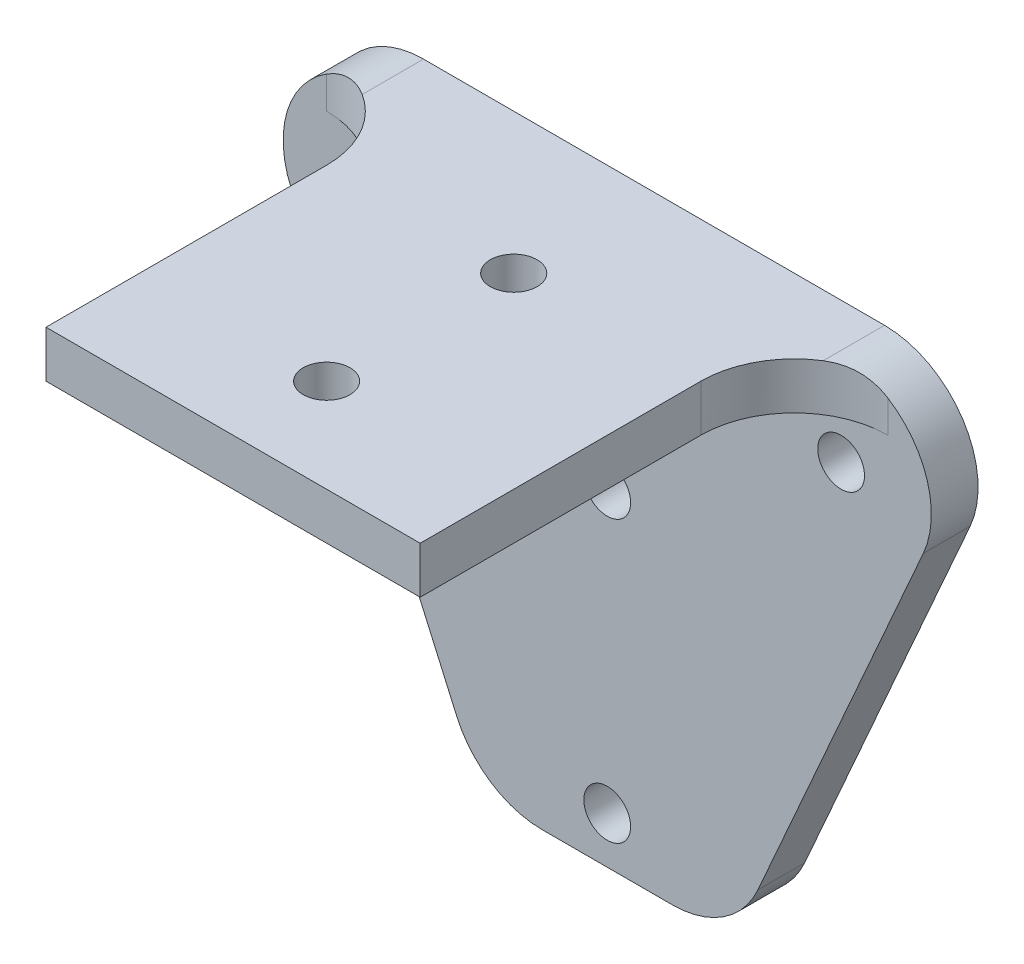
SolidWorks part; units mm, degrees
ref_plane "Plan de face" through (0, 0, 0) normal (0, 0, 1) x (1, 0, 0)
ref_plane "Plan de dessus" through (0, 0, 0) normal (0, 1, 0) x (1, 0, 0)
ref_plane "Plan de droite" through (0, 0, 0) normal (1, 0, 0) x (0, 0, -1)
sketch "Sketch1" plane through (0, 0, 0) normal (0, 0, 1) x (1, 0, 0)
  line L1 (0, 0) -> (80, 0) construction
  line L2 (0, 0) -> (0, 90) construction
  line L4 (80, 0) -> (80, 90) construction
  line L5 (60, 85) -> (20, 85) construction
  line L6 (60, 85) -> (60, 45) construction
  line L7 (60, 45) -> (20, 45) construction
  line L8 (0, 90) -> (80, 90)
  line L9 (80, 90) -> (53.4674, 30)
  line L10 (53.4674, 30) -> (26.5326, 30)
  line L11 (26.5326, 30) -> (0, 90)
  line L12 (0, 90) -> (80, 90) construction
  line L13 (20, 85) -> (20, 45) construction
  circle A1 centre (15, 80) radius 2.5
  circle A2 centre (65, 80) radius 2.5
  circle A3 centre (40, 35) radius 2.5
  circle A9 centre (40, 65) radius 2.5
  point P1 (40, 85)
  point P5 (40, 90)
  point P20 (0, 90)
  point P21 (0, 0)
  point P22 (60, 65)
  point P23 (0, 0)
  point P24 (26.5326, 30)
  point P25 (40, 30)
  dimension "D4" = 5
  dimension "D7" = 5
  dimension "5" = 5
  dimension "D8" = 5
  dimension "D9" = 5
  dimension "D1" = 90
  dimension "D2" = 80
  dimension "D3" = 45
  dimension "D5" = 40
  dimension "D6" = 40
  dimension "D10" = 5
  dimension "D11" = 10
  dimension "D12" = 25
  dimension "D13" = 25
extrude "Boss-Extrude1" add sketch "Sketch1" along normal blind 5
fillet "Fillet1" radius 10 4 edges at (26.5326, 30, 2.5) (53.4674, 30, 2.5) (80, 90, 2.5) (0, 90, 2.5)
sketch "Sketch2" plane through (0, 0, 5) normal (0, 0, 1) x (1, 0, 0)
  line L0 (64.6438, 90) -> (15.3562, 90) construction
  line L1 (20, 90) -> (60, 90)
  line L2 (20, 90) -> (20, 85)
  line L3 (20, 85) -> (60, 85)
  line L4 (60, 90) -> (60, 85)
  line L5 (64.6438, 90) -> (15.3562, 90) construction
  point P6 (40, 90)
  point P9 (40, 90)
  dimension "D1" = 5
  dimension "D2" = 40
extrude "Boss-Extrude2" add sketch "Sketch2" along normal blind 40
sketch "Sketch3" plane through (0, 90, 0) normal (0, 1, 0) x (1, 0, 0)
  line L0 (64.6438, 0) -> (15.3562, 0) construction
  circle A0 centre (40, -15) radius 2.5
  circle A1 centre (40, -35) radius 2.5
  point P7 (40, 0)
  dimension "D1" = 5
  dimension "D2" = 5
  dimension "D3" = 20
  dimension "D4" = 15
extrude "Cut-Extrude1" cut sketch "Sketch3" against normal through all
fillet "Fillet3" radius 10 2 edges at (60, 87.5, 5) (20, 87.5, 5)
sketch "Sketch4" plane through (0, 0, 0) normal (0, 0, -1) x (-1, 0, 0)
  line L0 (-40, 30) -> (-40, 90) construction
  line L1 (-35.0224, 37) -> (-33.0224, 37)
  line L2 (-35.0224, 37) -> (-35.0224, 30)
  line L3 (-35.0224, 30) -> (-33.0224, 30)
  line L4 (-33.0224, 37) -> (-33.0224, 30)
  line L9 (-33.0446, 30) -> (-46.9554, 30) construction
  line L10 (-64.6438, 90) -> (-15.3562, 90) construction
  line L11 (-44.9776, 30) -> (-46.9776, 30)
  line L12 (-46.9776, 37) -> (-46.9776, 30)
  line L13 (-44.9776, 37) -> (-46.9776, 37)
  line L14 (-44.9776, 37) -> (-44.9776, 30)
  point P10 (-32.9587, 32.2762)
  point P15 (-44.9776, 30)
  dimension "D1" = 2
  dimension "D2" = 7
extrude "Boss-Extrude3" add sketch "Sketch4" along normal blind 8
sketch "Sketch5" plane through (46.9776, 0, 0) normal (1, 0, 0) x (0, 0, -1)
  line L0 (8, 37) -> (0, 37) construction
  line L1 (1.125, 36) -> (7.125, 36)
  line L2 (1.125, 36) -> (1.125, 31)
  line L3 (1.125, 31) -> (7.125, 31)
  line L4 (7.125, 36) -> (7.125, 31)
  dimension "D1" = 6
  dimension "D2" = 5
  dimension "D3" = 1
extrude "Cut-Extrude2" cut sketch "Sketch5" against normal through all both and the other way through all
